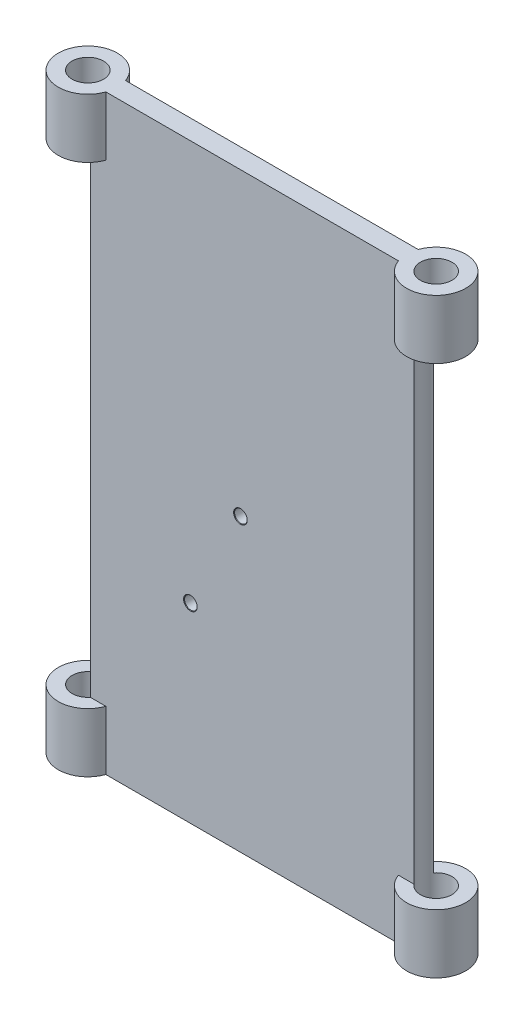
SolidWorks part; units mm, degrees
ref_plane "정면" through (0, 0, 0) normal (0, 0, 1) x (1, 0, 0)
ref_plane "윗면" through (0, 0, 0) normal (0, 1, 0) x (1, 0, 0)
ref_plane "우측면" through (0, 0, 0) normal (1, 0, 0) x (0, 0, -1)
sketch "스케치1" plane through (0, 0, 0) normal (0, 0, 1) x (1, 0, 0)
  line L1 (0, 0) -> (88.39, 0)
  line L2 (0, 0) -> (0, 150)
  line L3 (0, 150) -> (88.39, 150)
  line L4 (88.39, 0) -> (88.39, 150)
  dimension "D1" = 88.39
  dimension "D2" = 150
extrude "보스-돌출1" add sketch "스케치1" along normal blind 5
sketch "스케치2" plane through (0, 150, 0) normal (0, 1, 0) x (1, 0, 0)
  line L0 (88.39, -5) -> (88.39, 0) construction
  line L1 (0, -5) -> (0, 0) construction
  circle A0 centre (88.39, -2.5) radius 7.5
  circle A1 centre (0, -2.5) radius 7.5
  dimension "D1" = 15
  dimension "D2" = 15
extrude "보스-돌출2" add sketch "스케치2" against normal blind 15
hole_wizard "구멍1" positions "스케치3" profile "스케치4" legacy end condition through all
sketch "스케치3" plane through (0, 150, 0) normal (0, 1, 0) x (1, 0, 0)
  point P0 (0, -2.5)
  point P3 (88.39, -2.5)
sketch "스케치4" plane through (0, 150, 2.5) normal (1, 0, 0) x (0, 0, 1)
  line L0 (0, 0) -> (0, 150)
  line L1 (0, 150) -> (4, 150)
  line L2 (4, 150) -> (4, 0)
  line L3 (4, 0) -> (0, 0)
  line L4 (0, 110) -> (0, -10) construction
  dimension "지름" = 8
  dimension "깊이" = 150
sketch "스케치6" plane through (0, 0, 0) normal (0, 0, -1) x (-1, 0, 0)
  line L0 (-44.195, 150) -> (-44.195, -8.7542) construction
  line L1 (-81.3189, 150) -> (-7.0711, 150) construction
sketch "스케치7" plane through (0, 0, 0) normal (0, -1, 0) x (1, 0, 0)
  line L0 (81.3189, 0) -> (85.2675, 0)
  line L1 (81.3189, 5) -> (85.2675, 5)
  line L2 (85.2675, 5) -> (3.1225, 5)
  line L3 (3.1225, 0) -> (85.2675, 0)
  line L6 (3.1225, 5) -> (7.0711, 5)
  line L7 (3.1225, 0) -> (7.0711, 0)
  arc A2 (3.1225, 0) -> (3.1225, 5) centre (0, 2.5) ccw
  arc A3 (85.2675, 5) -> (85.2675, 0) centre (88.39, 2.5) ccw
  arc A4 (3.1225, 0) -> (3.1225, 5) centre (0, 2.5) ccw
  arc A5 (85.2675, 5) -> (85.2675, 0) centre (88.39, 2.5) ccw
  arc A6 (7.0711, 5) -> (7.0711, 0) centre (0, 2.5) ccw construction
  arc A8 (7.0711, 5) -> (7.0711, 0) centre (0, 2.5) ccw
  arc A10 (81.3189, 0) -> (81.3189, 5) centre (88.39, 2.5) ccw construction
  arc A12 (81.3189, 0) -> (81.3189, 5) centre (88.39, 2.5) ccw
  dimension "D1" = 0
extrude "보스-돌출3" add sketch "스케치7" against normal blind 15
sketch "스케치8" plane through (0, 15, 0) normal (0, 1, 0) x (1, 0, 0)
  circle A0 centre (0, -2.5) radius 4 construction
  circle A1 centre (88.39, -2.5) radius 4 construction
  circle A2 centre (0, -2.5) radius 4
  circle A3 centre (88.39, -2.5) radius 4
extrude "컷-돌출1" cut sketch "스케치8" against normal through all
hole_wizard "M3 여유 구멍1" positions "스케치11" profile "스케치12" hole size "M3" standard "ISO" end condition through all
sketch "스케치11" plane through (0, 0, 5) normal (0, 0, 1) x (1, 0, 0)
  line L0 (3.1225, 135) -> (3.1225, 15) construction
  line L1 (81.3189, 150) -> (7.0711, 150) construction
  point P0 (41.2225, 73.8)
  point P2 (28.5225, 48.4)
  dimension "D1" = 25.4
  dimension "D2" = 12.7
  dimension "D3" = 25.4
  dimension "D4" = 76.2
sketch "스케치12" plane through (41.2225, 73.8, 5) normal (1, 0, 0) x (0, -1, 0)
  line L0 (0, 0) -> (0, 10)
  line L1 (0, 10) -> (1.6, 10)
  line L2 (1.6, 10) -> (1.6, 0.125)
  line L3 (1.6, 0.125) -> (1.725, 0)
  line L5 (1.725, 0) -> (0, 0)
  line L6 (-1.6, 0.125) -> (-1.725, 0) construction
  line L11 (0, -6.35) -> (0, 107.95) construction
  dimension "관통 구멍 지름" = 3.2
  dimension "관통 구멍 깊이" = 10
  dimension "표면 카운터싱크 지름" = 3.45
  dimension "표면 카운터싱크 각도" = 90
